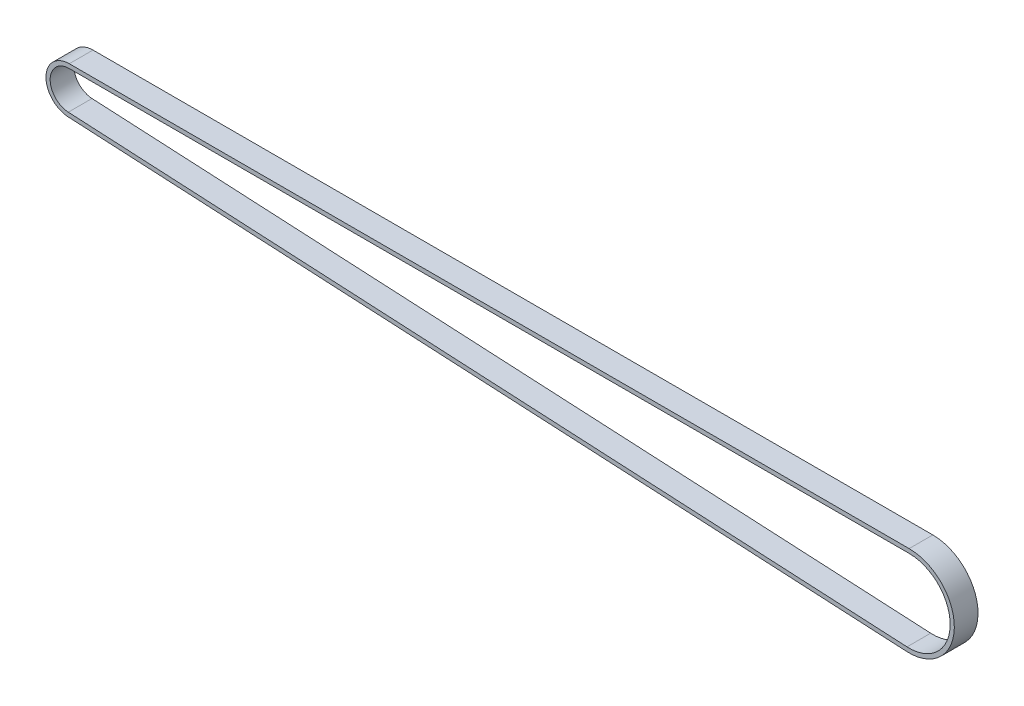
SolidWorks part; units mm, degrees
ref_plane "Front Plane" through (0, 0, 0) normal (0, 0, 1) x (1, 0, 0)
ref_plane "Top Plane" through (0, 0, 0) normal (0, 1, 0) x (1, 0, 0)
ref_plane "Right Plane" through (0, 0, 0) normal (1, 0, 0) x (0, 0, -1)
sketch "Sketch1" plane through (0, 0, 0) normal (0, 0, 1) x (1, 0, 0)
  line L0 (0, 5.8213) -> (225.1456, 5.8213) construction
  line L1 (225.1456, -5.8627) -> (225.1456, 5.8213) construction
  line L2 (-0.303, -5.8134) -> (224.5375, -17.5309) construction
  line L3 (-0.3254, -6.2446) -> (224.515, -17.9621)
  line L4 (0, 6.2531) -> (225.1456, 6.2531)
  line L5 (0, 5.1355) -> (225.1456, 5.1355)
  line L6 (-0.2673, -5.1285) -> (224.5732, -16.846)
  arc A0 (0, 5.8213) -> (-0.303, -5.8134) centre (0, 0) ccw construction
  arc A1 (224.5375, -17.5309) -> (225.1456, 5.8213) centre (225.1456, -5.8627) ccw construction
  arc A2 (0, 6.2531) -> (-0.3254, -6.2446) centre (0, 0) ccw
  arc A3 (224.515, -17.9621) -> (225.1456, 6.2531) centre (225.1456, -5.8627) ccw
  arc A4 (224.5732, -16.846) -> (225.1456, 5.1355) centre (225.1456, -5.8627) ccw
  arc A5 (0, 5.1355) -> (-0.2673, -5.1285) centre (0, 0) ccw
  dimension "D1" = 23.368
  dimension "D2" = 11.6425
  dimension "D3" = 225.1456
  dimension "D4" = 0.4318
  dimension "D5" = 0.6858
extrude "Boss-Extrude1" add sketch "Sketch1" along normal blind 6.35
